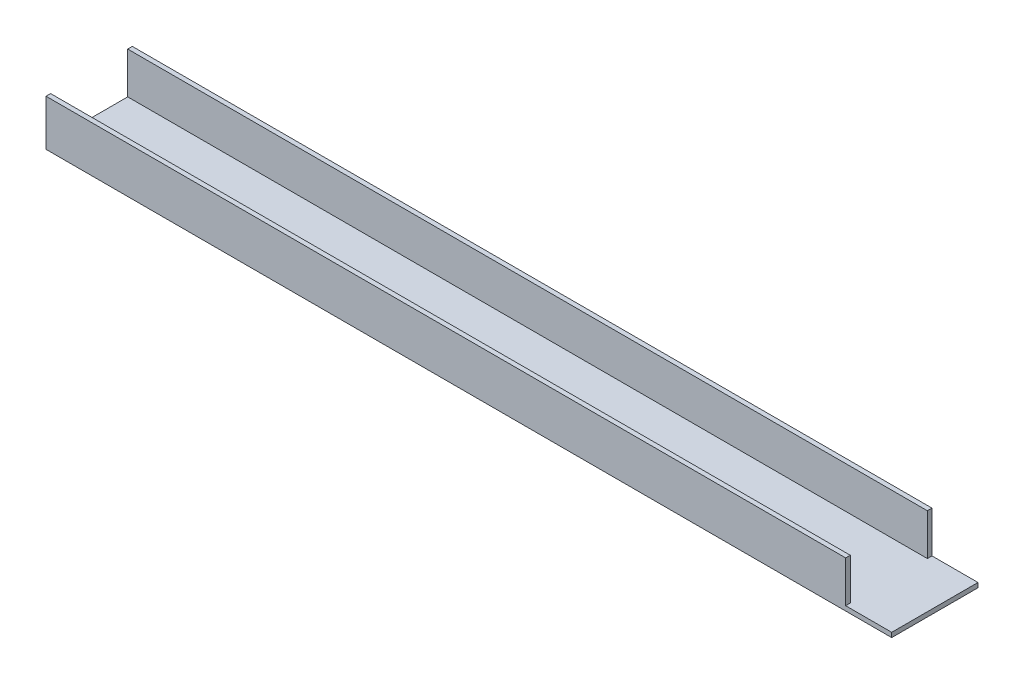
SolidWorks part; units mm, degrees
ref_plane "정면" through (0, 0, 0) normal (0, 0, 1) x (1, 0, 0)
ref_plane "윗면" through (0, 0, 0) normal (0, 1, 0) x (1, 0, 0)
ref_plane "우측면" through (0, 0, 0) normal (1, 0, 0) x (0, 0, -1)
sketch "스케치1" plane through (0, 0, 0) normal (0, 1, 0) x (1, 0, 0)
  line L1 (0, 0) -> (735, 0)
  line L2 (0, 0) -> (0, 75)
  line L3 (0, 75) -> (735, 75)
  line L4 (735, 0) -> (735, 75)
  dimension "D1" = 735
  dimension "D2" = 75
extrude "보스-돌출1" add sketch "스케치1" along normal blind 4
sketch "스케치2" plane through (0, 4, 0) normal (0, 1, 0) x (1, 0, 0)
  line L0 (0, 0) -> (735, 0) construction
  line L1 (0, 0) -> (695, 0)
  line L2 (0, 0) -> (0, 4)
  line L3 (0, 4) -> (695, 4)
  line L4 (695, 0) -> (695, 4)
  line L5 (735, 75) -> (0, 75) construction
  line L6 (695, 75) -> (0, 75)
  line L7 (695, 75) -> (695, 71)
  line L8 (695, 71) -> (0, 71)
  line L9 (0, 75) -> (0, 71)
  point P12 (0, 0)
  dimension "D1" = 4
  dimension "D2" = 4
  dimension "D3" = 695
extrude "보스-돌출2" add sketch "스케치2" along normal blind 36
